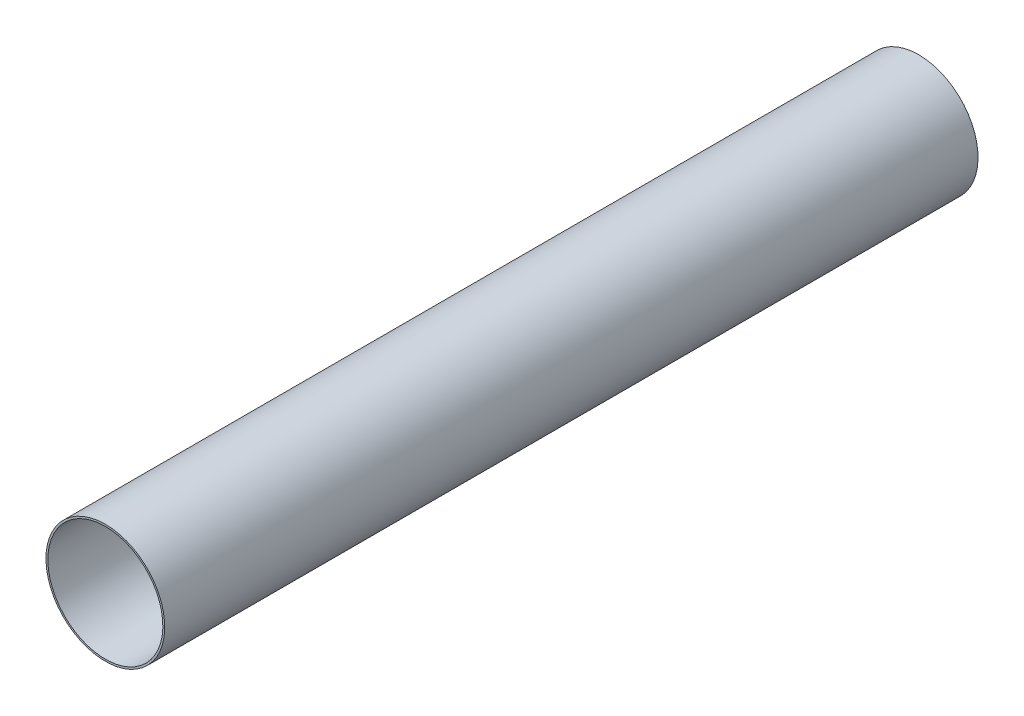
SolidWorks part; units mm, degrees
ref_plane "Plan de face" through (0, 0, 0) normal (0, 0, 1) x (1, 0, 0)
ref_plane "Plan de dessus" through (0, 0, 0) normal (0, 1, 0) x (1, 0, 0)
ref_plane "Plan de droite" through (0, 0, 0) normal (1, 0, 0) x (0, 0, -1)
sketch "Esquisse2" plane through (0, 0, 0) normal (1, 0, 0) x (0, 0, -1)
  line L0 (-10, 51.1) -> (-10, 49.5)
  line L2 (-10, 49.5) -> (-710, 49.5)
  line L19 (-710, 49.5) -> (-710, 51.1)
  line L20 (-710, 51.1) -> (-10, 51.1)
  line L24 (0, 0) -> (-694.9162, 0) construction
  dimension "D1" = 10
  dimension "D2" = 700
  dimension "D3" = 1.6
  dimension "D4" = 99
revolve "Révolution1" add sketch "Esquisse2" angle 360 about L24
